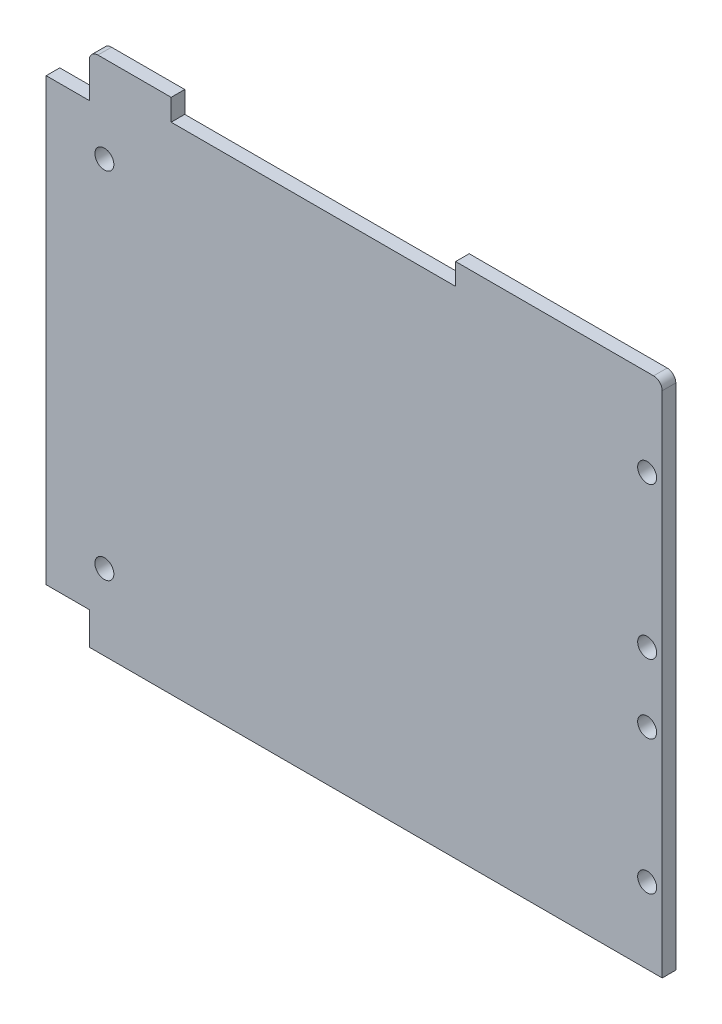
SolidWorks part; units mm, degrees
ref_plane "Front Plane" through (0, 0, 0) normal (0, 0, 1) x (1, 0, 0)
ref_plane "Top Plane" through (0, 0, 0) normal (0, 1, 0) x (1, 0, 0)
ref_plane "Right Plane" through (0, 0, 0) normal (1, 0, 0) x (0, 0, -1)
sketch "BPR2 PCB Outline" plane through (0, 0, 0) normal (0, 0, 1) x (1, 0, 0)
  line L0 (114.543, 6.6204) -> (102.643, 6.6204)
  line L1 (50.073, 67.1204) -> (114.543, 67.1204)
  line L2 (49.073, 66.1204) -> (49.073, 6.6204)
  line L3 (49.073, 6.6204) -> (82.643, 6.6204)
  line L4 (115.543, 66.1204) -> (115.543, 7.6204)
  line L9 (82.643, 6.6204) -> (102.643, 6.6204)
  arc A0 (114.543, 6.6204) -> (115.543, 7.6204) centre (114.543, 7.6204) ccw
  arc A1 (114.543, 67.1204) -> (115.543, 66.1204) centre (114.543, 66.1204) cw
  arc A2 (50.073, 67.1204) -> (49.073, 66.1204) centre (50.073, 66.1204) ccw
  point P6 (115.543, 6.6204)
  point P9 (115.543, 67.1204)
  point P12 (49.073, 67.1204)
  dimension "D2" = 66.47
  dimension "D4" = 11.9
  dimension "D3" = 1
  dimension "D1" = 60.5
sketch "23" plane through (0, 0, 0) normal (0, 0, 1) x (1, 0, 0)
  point P0 (0, 0)
extrude "Boss-Extrude1" add sketch "BPR2 PCB Outline" against normal blind 1.5748
sketch "Sketch3" plane through (0, 0, 0) normal (0, 0, 1) x (1, 0, 0)
  line L0 (115.543, 7.6204) -> (115.543, 66.1204) construction
  line L1 (49.073, 6.6204) -> (115.543, 6.6204)
  line L2 (49.073, 6.6204) -> (49.073, 11.9564)
  line L3 (49.073, 11.9564) -> (115.543, 11.9564)
  line L4 (115.543, 6.6204) -> (115.543, 11.9564)
extrude "Boss-Extrude2" add sketch "Sketch3" against normal blind 1.575
sketch "Sketch4" plane through (0, 0, 0) normal (0, 0, 1) x (1, 0, 0)
  line L1 (49.073, 6.6204) -> (115.543, 6.6204)
  line L2 (49.073, 6.6204) -> (49.073, 7.1204)
  line L3 (49.073, 7.1204) -> (115.543, 7.1204)
  line L4 (115.543, 6.6204) -> (115.543, 7.1204)
  dimension "D1" = 0.5
extrude "Cut-Extrude1" cut sketch "Sketch4" against normal through all
hole_wizard "M2 Clearance Hole1" positions "Sketch1" profile "Sketch2" hole size "M2" standard "ISO" end condition through all
sketch "Sketch1" plane through (32.7629, 104.0075, -6.5748) normal (0, 0, -1) x (1, 0, 0)
  point P0 (18.0601, 88.112)
  point P3 (18.0601, 46.962)
  point P6 (81.0301, 46.962)
  point P9 (81.0301, 64.537)
  point P12 (81.0301, 88.112)
  point P15 (81.0301, 72.537)
sketch "Sketch2" plane through (50.823, 15.8954, -6.5748) normal (1, 0, 0) x (0, 1, 0)
  line L0 (0, 0) -> (0, 6.5748)
  line L1 (0, 6.5748) -> (1.1, 6.5748)
  line L2 (1.1, 6.5748) -> (1.1, 0)
  line L3 (1.1, 0) -> (0, 0)
  line L4 (0, -6.35) -> (0, 107.95) construction
  dimension "Thru Hole Dia." = 2.2
  dimension "Thru Hole Depth" = 6.5748
sketch "Sketch5" plane through (0, 0, 0) normal (0, 0, 1) x (1, 0, 0)
  line L0 (-957.9863, 62.0454) -> (49042.0137, 62.0454) construction
  line L1 (43.404, 10.8954) -> (50043.404, 10.8954) construction
  line L2 (44.073, -936.3675) -> (44.073, 49063.6325) construction
  line L3 (49.073, 66.1204) -> (49.073, 7.1204) construction
  line L4 (49.073, -937.9546) -> (49.073, 49062.0454) construction
  line L6 (49.073, 62.0454) -> (44.073, 62.0454)
  line L7 (49.073, 62.0454) -> (49.073, 10.8954)
  line L8 (49.073, 10.8954) -> (44.073, 10.8954)
  line L9 (44.073, 62.0454) -> (44.073, 10.8954)
  dimension "D1" = 5
  dimension "D2" = 5
  dimension "D3" = 5
extrude "Boss-Extrude3" add sketch "Sketch5" against normal blind 1.575
sketch "Sketch6" plane through (0, 0, 0) normal (0, 0, 1) x (1, 0, 0)
  line L0 (91.573, -921.7746) -> (91.573, 49078.2254) construction
  line L1 (-911.3722, 64.6204) -> (49088.6278, 64.6204) construction
  line L3 (114.543, 67.1204) -> (50.073, 67.1204) construction
  line L4 (58.573, -929.0289) -> (58.573, 49070.9711) construction
  line L5 (-934.8666, 67.1204) -> (49065.1334, 67.1204) construction
  line L7 (58.573, 64.6204) -> (91.573, 64.6204)
  line L8 (58.573, 64.6204) -> (58.573, 67.1204)
  line L9 (58.573, 67.1204) -> (91.573, 67.1204)
  line L10 (91.573, 64.6204) -> (91.573, 67.1204)
  dimension "D1" = 9.5
  dimension "D2" = 2.5
  dimension "D3" = 33
extrude "Cut-Extrude2" cut sketch "Sketch6" against normal through all
equation "\"adjustment\"= 10mm"
